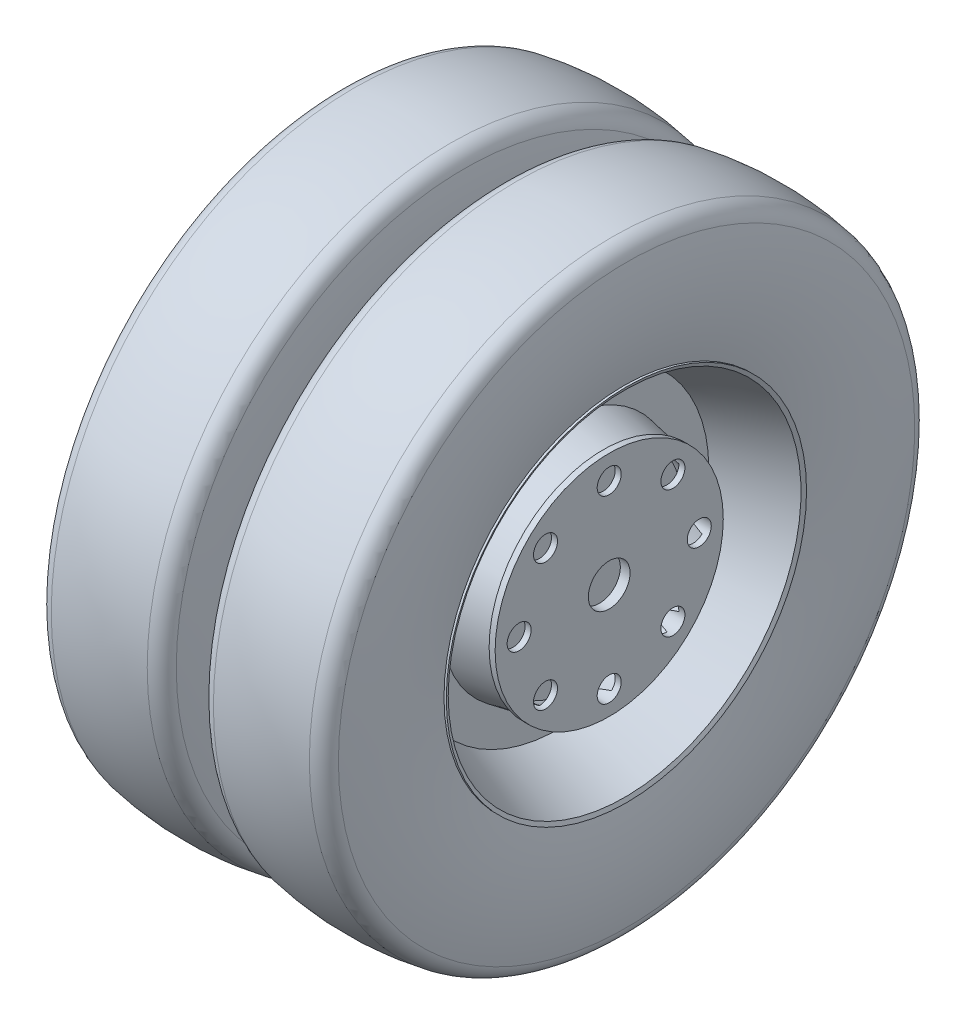
SolidWorks part; units mm, degrees
ref_plane "Front Plane" through (0, 0, 0) normal (0, 0, 1) x (1, 0, 0)
ref_plane "Top Plane" through (0, 0, 0) normal (0, 1, 0) x (1, 0, 0)
ref_plane "Right Plane" through (0, 0, 0) normal (1, 0, 0) x (0, 0, -1)
sketch "Sketch1" plane through (0, 0, 0) normal (0, 0, 1) x (1, 0, 0)
  line L0 (0, 300) -> (0, 500) construction
  line L1 (-70, 500) -> (-270, 500) construction
  line L2 (0, 500) -> (200, 500) construction
  line L3 (200, 500) -> (200, 300) construction
  line L4 (200, 300) -> (-270, 300) construction
  line L5 (-270, 300) -> (-270, 500) construction
  line L6 (-70, 500) -> (-70, 300) construction
  line L7 (-195, 0) -> (158.9556, 0)
  line L8 (175.1653, 34.7469) -> (175.1653, 190)
  line L9 (175.1653, 190) -> (165.1653, 190)
  line L10 (165.1653, 190) -> (165.1653, 181.3462)
  line L11 (165.1653, 181.3462) -> (90.6934, 194.5739)
  line L12 (90.6934, 194.5739) -> (90.6934, 250.3611)
  line L13 (90.6934, 250.3611) -> (200.8418, 293.7591)
  line L14 (200.8418, 293.7591) -> (203.8373, 300)
  line L15 (203.8373, 300) -> (200, 300)
  line L16 (0, 300) -> (0, 213.6148)
  line L17 (0, 213.6148) -> (-70, 213.6148)
  line L18 (-70, 213.6148) -> (-70, 300)
  line L19 (-270, 300) -> (-220, 250)
  line L20 (-220, 250) -> (-220, 215)
  line L21 (-220, 215) -> (-195, 215)
  line L22 (-195, 215) -> (-195, 0)
  line L23 (165.1653, 152.0402) -> (165.1653, 61.2518)
  line L24 (165.1653, 61.2518) -> (125.1653, 61.2518)
  line L25 (125.1653, 61.2518) -> (125.1653, 172.1703)
  line L26 (125.1653, 172.1703) -> (165.1653, 165.0656)
  line L27 (165.1653, 165.0656) -> (165.1653, 152.0402)
  line L28 (175.1653, 34.7469) -> (158.9556, 34.7469)
  line L29 (158.9556, 34.7469) -> (158.9556, 0)
  arc A0 (204.1008, 479.9045) -> (200, 300) centre (-238.7482, 400) cw
  arc A1 (20.0955, 504.1008) -> (179.9045, 504.1008) centre (100, 61.2518) cw
  arc A2 (-90.0955, 504.1008) -> (-249.9045, 504.1008) centre (-170, 61.2518) ccw
  arc A3 (-274.1008, 479.9045) -> (-270, 300) centre (168.7482, 400) ccw
  arc A4 (-65.8992, 479.9045) -> (-70, 300) centre (-508.7482, 400) cw
  arc A5 (-4.1008, 479.9045) -> (0, 300) centre (438.7482, 400) ccw
  arc A6 (204.1008, 479.9045) -> (179.9045, 504.1008) centre (174.5775, 474.5775) ccw
  arc A7 (-4.1008, 479.9045) -> (20.0955, 504.1008) centre (25.4225, 474.5775) cw
  arc A8 (-90.0955, 504.1008) -> (-65.8992, 479.9045) centre (-95.4225, 474.5775) cw
  arc A9 (-249.9045, 504.1008) -> (-274.1008, 479.9045) centre (-244.5775, 474.5775) ccw
  dimension "D6" = 450
  dimension "D18" = 30
  dimension "D1" = 500
  dimension "D2" = 200
  dimension "D3" = 200
  dimension "D4" = 70
  dimension "D5" = 200
  dimension "D7" = 470
  dimension "D8" = 50
  dimension "D9" = 45
  dimension "D10" = 215
  dimension "D11" = 25
  dimension "D13" = 50
  dimension "D14" = 10
  dimension "D15" = 3.8373
  dimension "D16" = 6.2409
  dimension "D17" = 0.8418
revolve "Revolve1" add sketch "Sketch1" angle 360 about L7
sketch "Sketch2" plane through (175.1653, 0, 0) normal (1, 0, 0) x (0, 0, -1)
  circle A0 centre (0, 150) radius 20
  circle A1 centre (106.066, 106.066) radius 20
  circle A2 centre (150, 0) radius 20
  circle A3 centre (106.066, -106.066) radius 20
  circle A4 centre (0, -150) radius 20
  circle A5 centre (-106.066, -106.066) radius 20
  circle A6 centre (-150, 0) radius 20
  circle A7 centre (-106.066, 106.066) radius 20
  dimension "D2" = 40
  dimension "D1" = 150
  dimension "D3" = 8
extrude "Cut-Extrude1" cut sketch "Sketch2" against normal blind 50
sketch "Sketch3" plane through (125.1653, 0, 0) normal (1, 0, 0) x (0, 0, -1)
  circle A0 centre (0, 150) radius 15
  circle A1 centre (106.066, 106.066) radius 15
  circle A2 centre (150, 0) radius 15
  circle A3 centre (106.066, -106.066) radius 15
  circle A4 centre (0, -150) radius 15
  circle A5 centre (-106.066, -106.066) radius 15
  circle A6 centre (-150, 0) radius 15
  circle A7 centre (-106.066, 106.066) radius 15
  dimension "D1" = 30
  dimension "D2" = 8
extrude "Cut-Extrude2" cut sketch "Sketch3" against normal through all
